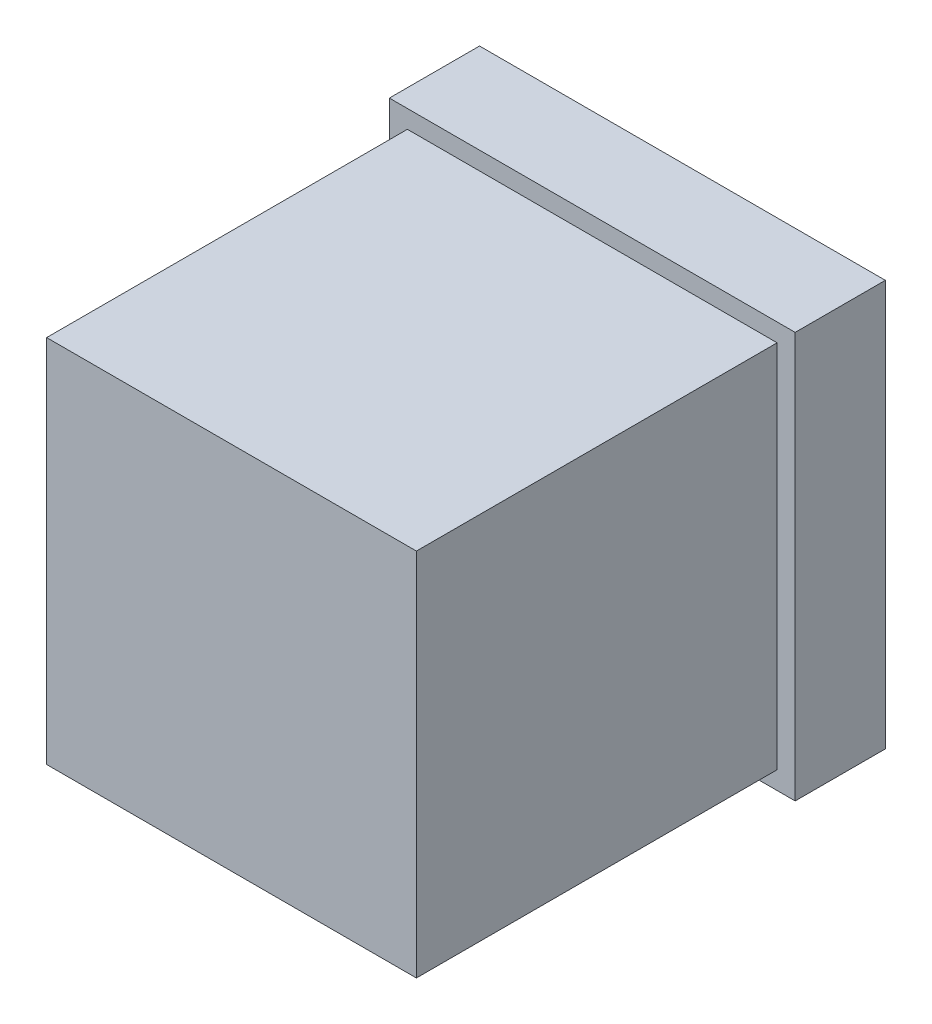
SolidWorks part; units mm, degrees
ref_plane "Alzado" through (0, 0, 0) normal (0, 0, 1) x (1, 0, 0)
ref_plane "Planta" through (0, 0, 0) normal (0, 1, 0) x (1, 0, 0)
ref_plane "Vista lateral" through (0, 0, 0) normal (1, 0, 0) x (0, 0, -1)
sketch "Croquis1" plane through (0, 0, 0) normal (0, 0, 1) x (1, 0, 0)
  line L1 (0, 0) -> (45, 0)
  line L2 (0, 0) -> (0, 45)
  line L3 (0, 45) -> (45, 45)
  line L4 (45, 0) -> (45, 45)
  dimension "D1" = 45
  dimension "D2" = 45
extrude "Saliente-Extruir1" add sketch "Croquis1" along normal blind 10
sketch "Croquis2" plane through (0, 0, 10) normal (0, 0, 1) x (1, 0, 0)
  line L0 (0, 45) -> (0, 0) construction
  line L1 (2, 43) -> (43, 43)
  line L2 (2, 43) -> (2, 2)
  line L3 (2, 2) -> (43, 2)
  line L4 (43, 43) -> (43, 2)
  line L5 (45, 45) -> (0, 45) construction
  line L6 (45, 0) -> (45, 45) construction
  line L7 (0, 0) -> (45, 0) construction
  dimension "D1" = 2
  dimension "D2" = 2
  dimension "D3" = 2
  dimension "D4" = 2
extrude "Saliente-Extruir2" add sketch "Croquis2" along normal blind 40
